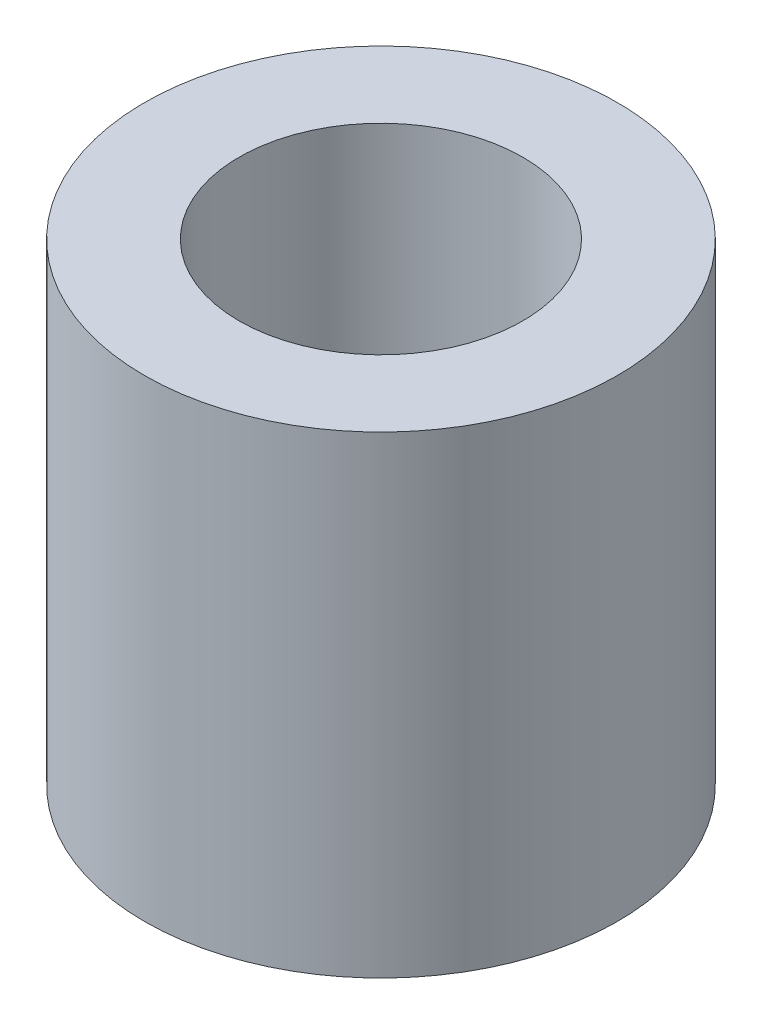
SolidWorks part; units mm, degrees
ref_plane "Front Plane" through (0, 0, 0) normal (0, 0, 1) x (1, 0, 0)
ref_plane "Top Plane" through (0, 0, 0) normal (0, 1, 0) x (1, 0, 0)
ref_plane "Right Plane" through (0, 0, 0) normal (1, 0, 0) x (0, 0, -1)
sketch "Sketch1" plane through (0, 0, 0) normal (0, 1, 0) x (1, 0, 0)
  circle A0 centre (0, 0) radius 1.5
  circle A1 centre (0, 0) radius 2.5
  dimension "D1" = 1
extrude "Boss-Extrude2" add sketch "Sketch1" along normal blind 5
